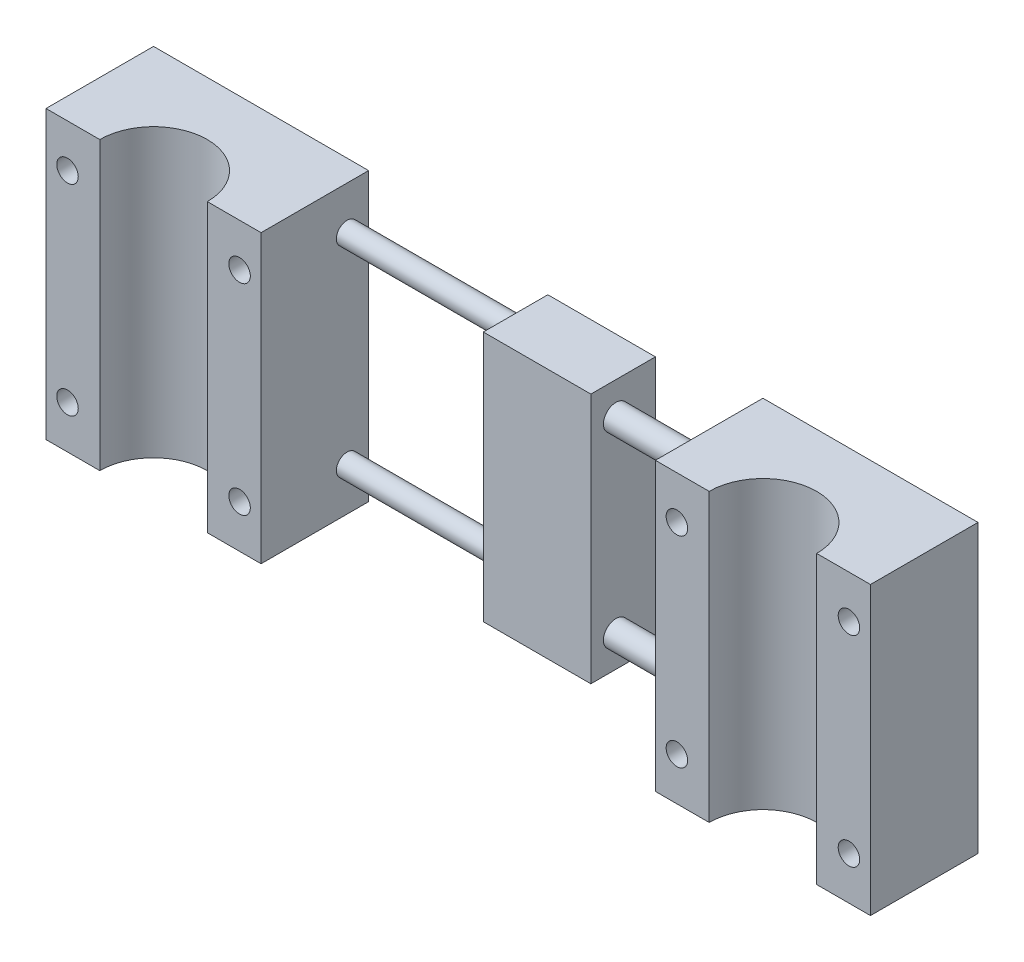
SolidWorks part; units mm, degrees
ref_plane "Front Plane" through (0, 0, 0) normal (0, 0, 1) x (1, 0, 0)
ref_plane "Top Plane" through (0, 0, 0) normal (0, 1, 0) x (1, 0, 0)
ref_plane "Right Plane" through (0, 0, 0) normal (1, 0, 0) x (0, 0, -1)
sketch "Sketch1" plane through (0, 0, 0) normal (0, 0, 1) x (1, 0, 0)
  line L1 (0, 0) -> (30, 0)
  line L2 (0, 0) -> (0, 40)
  line L3 (0, 40) -> (30, 40)
  line L4 (30, 0) -> (30, 40)
  dimension "D1" = 40
  dimension "D2" = 30
extrude "Boss-Extrude1" add sketch "Sketch1" along normal blind 15
sketch "Sketch2" plane through (0, 40, 0) normal (0, 1, 0) x (1, 0, 0)
  line L0 (30, -15) -> (0, -15) construction
  line L1 (7.5, -15) -> (22.5, -15)
  arc A0 (22.5, -15) -> (7.5, -15) centre (15, -15) ccw
  dimension "D1" = 15
extrude "Cut-Extrude1" cut sketch "Sketch2" against normal blind 49
sketch "Sketch3" plane through (0, 0, 15) normal (0, 0, 1) x (1, 0, 0)
  line L0 (7.5, 40) -> (0, 40) construction
  line L1 (0, 40) -> (0, 0) construction
  line L2 (30, 0) -> (30, 40) construction
  line L3 (30, 40) -> (22.5, 40) construction
  line L4 (22.5, 0) -> (30, 0) construction
  line L5 (0, 0) -> (7.5, 0) construction
  circle A0 centre (3, 34) radius 1.5
  circle A1 centre (3, 6) radius 1.5
  circle A2 centre (27, 34) radius 1.5
  circle A3 centre (27, 6) radius 1.5
  point P19 (26.25, 0)
  point P25 (3.75, 0)
  dimension "D1" = 3
  dimension "D2" = 3
  dimension "D3" = 3
  dimension "D4" = 3
  dimension "D5" = 6
  dimension "D6" = 3
  dimension "D7" = 3
  dimension "D8" = 6
  dimension "D9" = 6
  dimension "D10" = 3
  dimension "D11" = 3
  dimension "D12" = 6
extrude "Cut-Extrude2" cut sketch "Sketch3" against normal blind 49
sketch "Sketch4" plane through (30, 0, 0) normal (1, 0, 0) x (0, 0, -1)
  line L0 (-15, 40) -> (0, 40) construction
  line L1 (-15, 0) -> (0, 0) construction
  line L2 (0, 0) -> (0, 40) construction
  circle A0 centre (-3, 34) radius 1.5
  circle A1 centre (-3, 6) radius 1.5
  dimension "D1" = 3
  dimension "D2" = 3
  dimension "D3" = 6
  dimension "D4" = 6
  dimension "D5" = 3
  dimension "D6" = 3
extrude "Boss-Extrude2" add sketch "Sketch4" along normal blind 25
sketch "Sketch5" plane through (55, 0, 0) normal (1, 0, 0) x (0, 0, -1)
  line L0 (0, 0) -> (0, 40) construction
  line L1 (0, 37.5) -> (-9, 37.5)
  line L2 (0, 37.5) -> (0, 2.5)
  line L3 (0, 2.5) -> (-9, 2.5)
  line L4 (-9, 37.5) -> (-9, 2.5)
  circle A0 centre (-3, 34) radius 1.5 construction
  point P6 (-4.5, 37.5)
  dimension "D3" = 9
  dimension "D1" = 3.5
  dimension "D2" = 35
extrude "Boss-Extrude3" add sketch "Sketch5" along normal blind 15
sketch "Sketch6" plane through (70, 0, 0) normal (1, 0, 0) x (0, 0, -1)
  line L0 (0, 37.5) -> (-9, 37.5) construction
  line L1 (-9, 2.5) -> (0, 2.5) construction
  line L2 (-9, 37.5) -> (-9, 2.5) construction
  circle A0 centre (-5.5, 33) radius 1.75
  circle A1 centre (-5.5, 6.8875) radius 1.75
  point P8 (-4.5, 2.5)
  dimension "D1" = 3.5
  dimension "D2" = 3.5
  dimension "D3" = 4.5
  dimension "D4" = 4.5
  dimension "D5" = 3.5
  dimension "D6" = 3.5
extrude "Boss-Extrude4" add sketch "Sketch6" along normal blind 15
sketch "Sketch7" plane through (85, 0, 0) normal (1, 0, 0) x (0, 0, -1)
  line L1 (0, 40) -> (-15, 40)
  line L2 (0, 40) -> (0, 0)
  line L3 (0, 0) -> (-15, 0)
  line L4 (-15, 40) -> (-15, 0)
extrude "Boss-Extrude6" add sketch "Sketch7" along normal blind 30
sketch "Sketch9" plane through (0, 40, 0) normal (0, 1, 0) x (1, 0, 0)
  line L0 (115, -15) -> (85, -15) construction
  line L1 (92.5, -15) -> (107.5, -15)
  arc A0 (107.5, -15) -> (92.5, -15) centre (100, -15) ccw
  dimension "D1" = 15
extrude "Cut-Extrude3" cut sketch "Sketch9" against normal blind 59
sketch "Sketch10" plane through (0, 0, 15) normal (0, 0, 1) x (1, 0, 0)
  line L0 (92.5, 40) -> (85, 40) construction
  line L1 (85, 40) -> (85, 0) construction
  line L2 (115, 40) -> (115, 0) construction
  line L3 (115, 40) -> (107.5, 40) construction
  line L4 (115, 0) -> (107.5, 0) construction
  line L5 (92.5, 0) -> (85, 0) construction
  circle A0 centre (88, 34) radius 1.5
  circle A1 centre (112, 34) radius 1.5
  circle A2 centre (112, 6) radius 1.5
  circle A3 centre (88, 6) radius 1.5
  dimension "D1" = 3
  dimension "D2" = 6
  dimension "D3" = 3
  dimension "D4" = 3
  dimension "D5" = 6
  dimension "D6" = 3
  dimension "D7" = 6
  dimension "D8" = 6
  dimension "D9" = 3
extrude "Cut-Extrude4" cut sketch "Sketch10" against normal blind 59
sketch "Sketch14" plane through (0, 0, 0) normal (0, 0, -1) x (-1, 0, 0)
  line L0 (-100, 0) -> (-100, 40) construction
  line L1 (-107, 12) -> (-93, 12)
  line L2 (-107, 12) -> (-107, 28)
  line L3 (-107, 28) -> (-93, 28)
  line L4 (-93, 12) -> (-93, 28)
  line L5 (-107, 12) -> (-93, 28) construction
  line L6 (-107, 28) -> (-93, 12) construction
  line L7 (-115, 0) -> (-85, 0) construction
  point P0 (-100, 20)
  dimension "D1" = 16
  dimension "D2" = 14
  dimension "D3" = 12
ref_plane "Plane1" through (57.5, 0, 0) normal (1, 0, 0) x (0, 0, -1)
